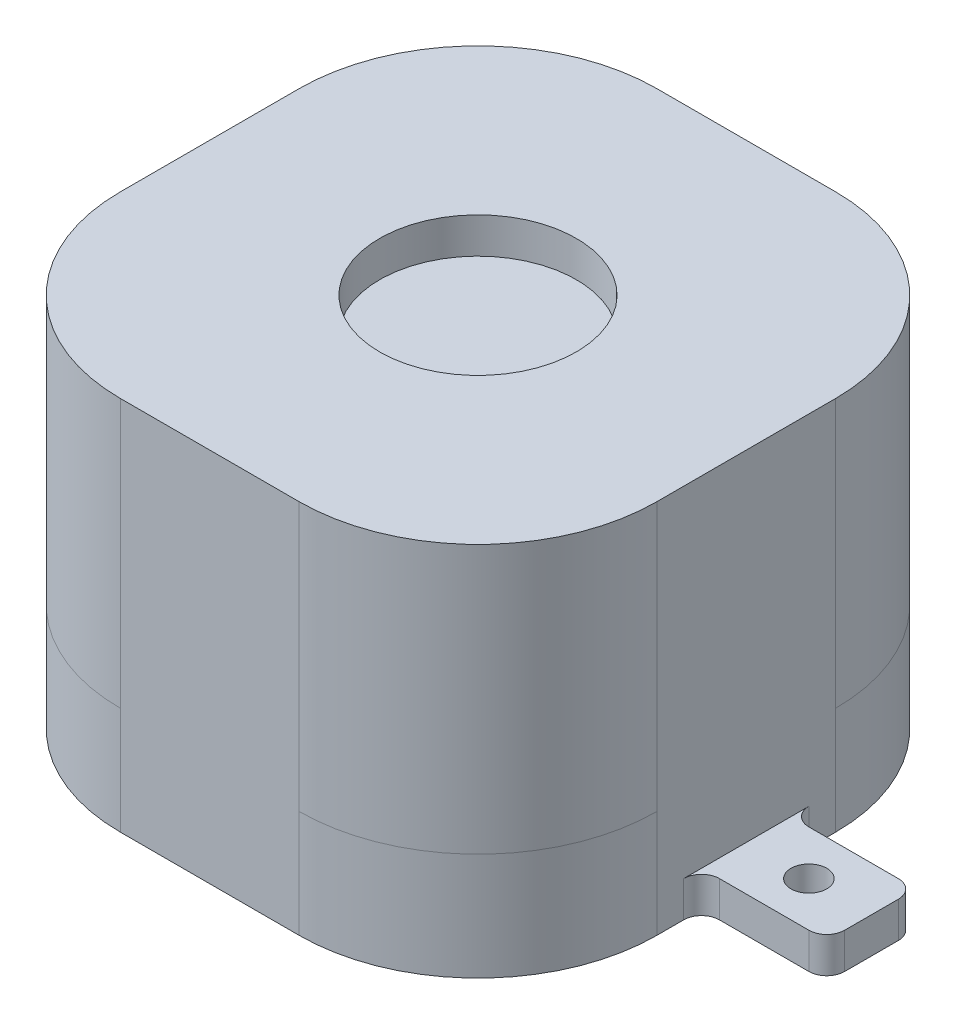
SolidWorks part; units mm, degrees
ref_plane "Front Plane" through (0, 0, 0) normal (0, 0, 1) x (1, 0, 0)
ref_plane "Top Plane" through (0, 0, 0) normal (0, 1, 0) x (1, 0, 0)
ref_plane "Right Plane" through (0, 0, 0) normal (1, 0, 0) x (0, 0, -1)
sketch "Sketch1" plane through (0, 0, 0) normal (0, 1, 0) x (1, 0, 0)
  line L1 (15, -15) -> (-15, -15)
  line L2 (15, -15) -> (15, 15)
  line L3 (15, 15) -> (-15, 15)
  line L4 (-15, -15) -> (-15, 15)
  line L5 (15, -15) -> (-15, 15) construction
  line L6 (15, 15) -> (-15, -15) construction
  point P0 (0, 0)
  dimension "D1" = 30
extrude "Boss-Extrude1" add sketch "Sketch1" along normal blind 6
fillet "Fillet1" radius 10 4 edges at (15, 3, 15) (15, 3, -15) (-15, 3, -15) (-15, 3, 15)
sketch "Sketch3" plane through (0, 0, 0) normal (0, -1, 0) x (1, 0, 0)
  line L0 (15, 5) -> (15, -5) construction
  line L1 (15, -2.5) -> (22, -2.5)
  line L2 (15, -2.5) -> (15, 2.5)
  line L3 (15, 2.5) -> (22, 2.5)
  line L4 (22, -2.5) -> (22, 2.5)
  line L5 (22, 0) -> (0, 0) construction
  circle A0 centre (18.5, 0) radius 1
  dimension "D3" = 2
  dimension "D1" = 5
  dimension "D2" = 7
  dimension "D4" = 18.5
extrude "Boss-Extrude2" add sketch "Sketch3" against normal blind 2
mirror "Mirror1" about plane through (0, 0, 0) normal (1, 0, 0) of "Boss-Extrude2"
fillet "Fillet3" radius 1 8 edges at (22, 1, -2.5) (15, 1, -2.5) (22, 1, 2.5) (15, 1, 2.5) (-15, 1, 2.5) (-22, 1, 2.5) (-15, 1, -2.5) (-22, 1, -2.5)
sketch "Sketch4" plane through (0, 6, 0) normal (0, 1, 0) x (1, 0, 0)
  line L1 (15, -15) -> (-15, -15)
  line L2 (15, -15) -> (15, 15)
  line L3 (15, 15) -> (-15, 15)
  line L4 (-15, -15) -> (-15, 15)
  line L5 (15, -15) -> (-15, 15) construction
  line L6 (15, 15) -> (-15, -15) construction
  point P0 (0, 0)
  dimension "D1" = 30
extrude "Boss-Extrude3" add sketch "Sketch4" along normal blind 15
fillet "Fillet4" radius 10 4 edges at (15, 13.5, 15) (15, 13.5, -15) (-15, 13.5, -15) (-15, 13.5, 15)
sketch "Sketch5" plane through (0, 21, 0) normal (0, 1, 0) x (1, 0, 0)
  circle A0 centre (0, 0) radius 5.5
  dimension "D1" = 11
extrude "Cut-Extrude2" cut sketch "Sketch5" against normal blind 2
